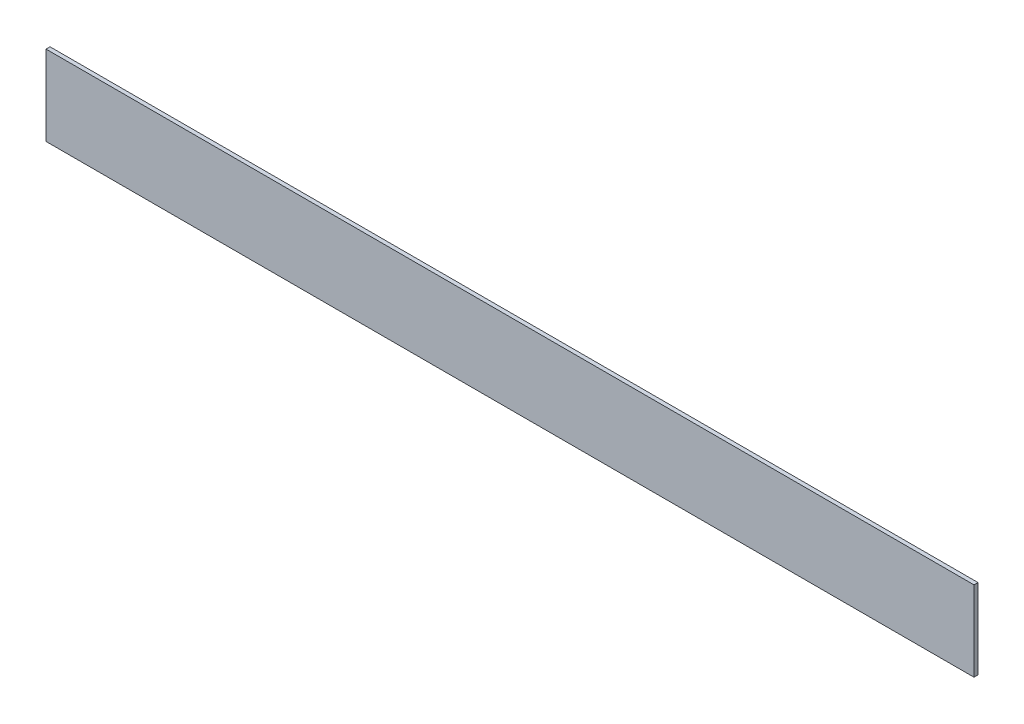
SolidWorks part; units mm, degrees
ref_plane "Plano frontal" through (0, 0, 0) normal (0, 0, 1) x (1, 0, 0)
ref_plane "Plano superior" through (0, 0, 0) normal (0, 1, 0) x (1, 0, 0)
ref_plane "Plano direito" through (0, 0, 0) normal (1, 0, 0) x (0, 0, -1)
sketch "Sketch1" plane through (0, 0, 0) normal (0, 0, 1) x (1, 0, 0)
  line L1 (1159.7196, 100) -> (-1159.7196, 100)
  line L2 (1159.7196, 100) -> (1159.7196, -100)
  line L3 (1159.7196, -100) -> (-1159.7196, -100)
  line L4 (-1159.7196, 100) -> (-1159.7196, -100)
  line L5 (1159.7196, 100) -> (-1159.7196, -100) construction
  line L6 (1159.7196, -100) -> (-1159.7196, 100) construction
  point P0 (0, 0)
extrude "Boss-Extrude1" add sketch "Sketch1" along normal blind 10
